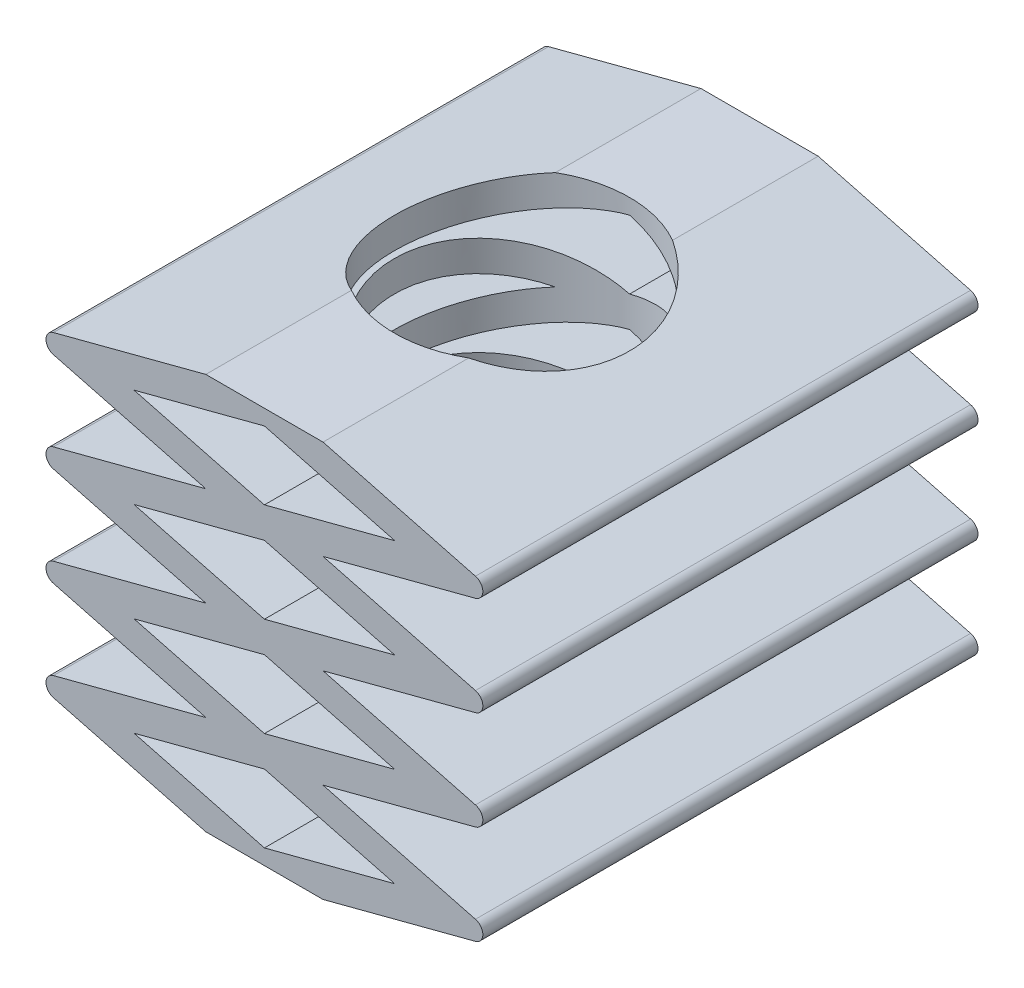
SolidWorks part; units mm, degrees
material "ABS"
ref_plane "Front Plane" through (0, 0, 0) normal (0, 0, 1) x (1, 0, 0)
ref_plane "Top Plane" through (0, 0, 0) normal (0, 1, 0) x (1, 0, 0)
ref_plane "Right Plane" through (0, 0, 0) normal (1, 0, 0) x (0, 0, -1)
sketch "Sketch1" plane through (0, 0, 0) normal (0, 0, 1) x (1, 0, 0)
  line L0 (0, 0) -> (4, 1.25)
  line L1 (4, 1.25) -> (0, 2.5)
  line L2 (0, 2.5) -> (1, 2.5)
  line L3 (1, 2.5) -> (5, 1.25)
  line L4 (5, 1.25) -> (1, 0)
  line L5 (1, 0) -> (0, 0)
  line L6 (5, 1.25) -> (4, 1.25) construction
  line L7 (0, 2.5) -> (0, 0) construction
  line L8 (5, 1.25) -> (0, 1.25) construction
  line L9 (2.5, 1.25) -> (2.5, 0.4687) construction
  line L10 (4, 0) -> (5, 0)
  line L11 (5, 0) -> (1, 1.25)
  line L12 (0, 1.25) -> (4, 0)
  line L13 (5, 2.5) -> (4, 2.5)
  line L14 (4, 2.5) -> (0, 1.25)
  line L15 (1, 1.25) -> (5, 2.5)
  line L16 (4, 5) -> (5, 5)
  line L17 (1, 5) -> (0, 5)
  line L18 (5, 3.75) -> (1, 5)
  line L19 (0, 5) -> (4, 3.75)
  line L20 (0, 3.75) -> (4, 5)
  line L21 (5, 5) -> (1, 3.75)
  line L22 (4, 3.75) -> (0, 2.5)
  line L23 (1, 2.5) -> (5, 3.75)
  line L24 (4, 2.5) -> (0, 3.75)
  line L25 (1, 3.75) -> (5, 2.5)
  dimension "D2" = 2.5
  dimension "D3" = 5
  dimension "D1" = 1
extrude "Boss-Extrude2" [suppressed] add sketch "Sketch1" along normal blind 5 contours L4 L12 L10 L11 | L15 L1 L0 L11 L4 L3 | L0 L12 L4 L11 | L12 L0 L5 L4 | L11 L15 L1 L14 L12 L0 | L1 L15 L3 L14 | L3 L15 L13 L14 | L14 L3 L2 L1 | L25 L23 L24 L13 | L23 L24 L22 L2 | L25 L22 L24 L23 | L25 L21 L19 L20 L24 L22 | L22 L25 L23 L18 L21 L19 | L21 L18 L20 L19 | L19 L20 L18 L17 | L21 L16 L20 L18
sketch "Sketch2" plane through (0, 0, 0) normal (0, 0, 1) x (1, 0, 0)
  line L0 (-1.1836, 0) -> (1.1836, 0)
  line L1 (0, 0) -> (0, 1) construction
  line L2 (1.1836, 0) -> (5, 1)
  line L3 (5, 1) -> (0, 1) construction
  line L4 (-1.1836, 0) -> (-5, 1)
  line L5 (-1.1836, 2) -> (1.1836, 2)
  line L6 (1.1836, 2) -> (5, 1)
  line L7 (-1.1836, 2) -> (-5, 1)
  line L8 (1.1836, 0) -> (-1.1836, 0)
  line L9 (-1.1836, 0) -> (2.6328, 1)
  line L10 (1.1836, 0) -> (-2.6328, 1)
  line L11 (-1.1836, 2) -> (2.6328, 1)
  line L12 (1.1836, 2) -> (-1.1836, 2)
  line L13 (1.1836, 2) -> (-2.6328, 1)
  point P13 (0, 0)
  dimension "D1" = 0.6
  dimension "D3" = 10
  dimension "D4" = 2
extrude "Boss-Extrude3" add sketch "Sketch2" along normal blind 10 contours L13 L11 L7 L4 L9 L10 | L6 L13 L11 L9 L10 L2 | L13 L5 L11 | L0 L10 L9
pattern_linear "LPattern1" count 4 spacing 2 along (0, 1, 0) of "Boss-Extrude3"
sketch "Sketch3" plane through (0, 0, 0) normal (0, -1, 0) x (1, 0, 0)
  line L0 (0, 0) -> (0, 10) construction
  line L1 (-1.1836, 10) -> (1.1836, 10) construction
  circle A0 centre (0, 5) radius 2.375
  dimension "D1" = 4.75
extrude "Cut-Extrude1" cut sketch "Sketch3" against normal through all
fillet "Fillet1" radius 0.2 8 edges at (-5, 1, 5) (-5, 3, 5) (-5, 5, 5) (-5, 7, 5) (5, 7, 5) (5, 5, 5) (5, 3, 5) (5, 1, 5)
